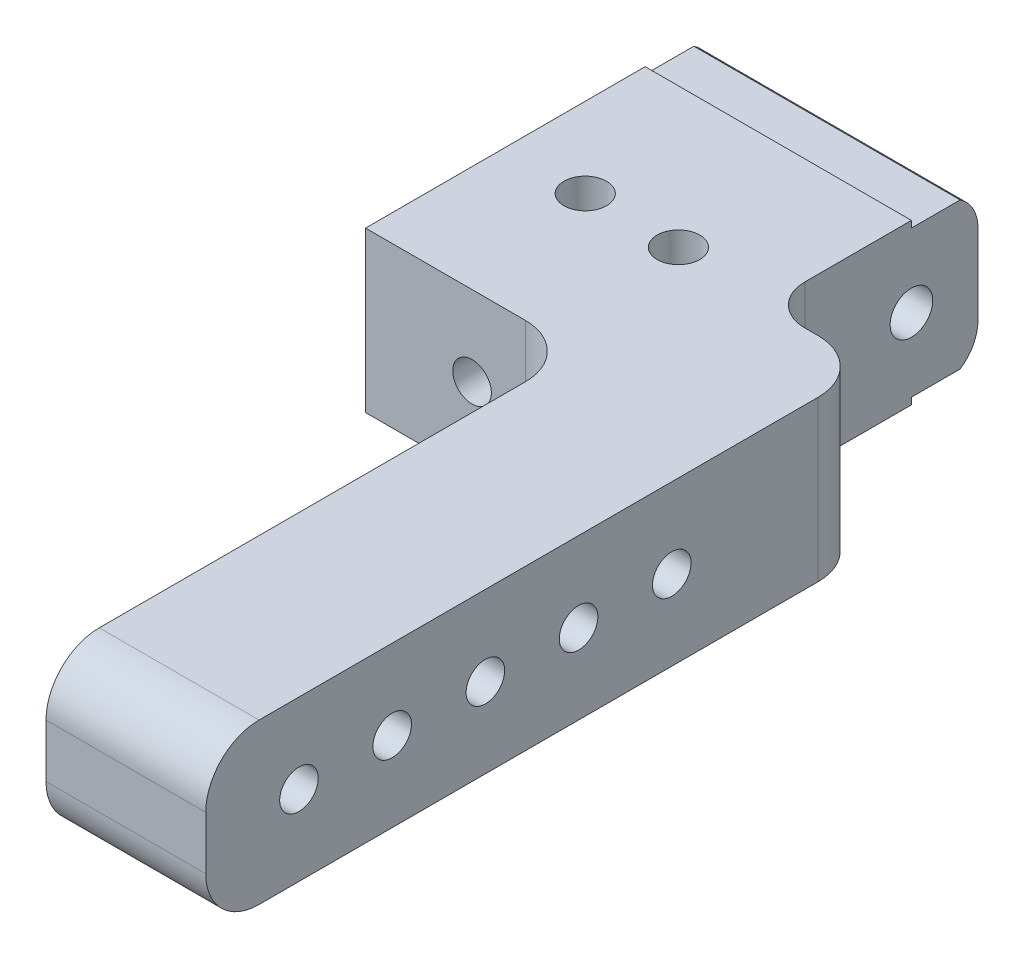
SolidWorks part; units mm, degrees
ref_plane "Front" through (0, 0, 0) normal (0, 0, 1) x (1, 0, 0)
ref_plane "Top" through (0, 0, 0) normal (0, 1, 0) x (1, 0, 0)
ref_plane "Right" through (0, 0, 0) normal (1, 0, 0) x (0, 0, -1)
sketch "Sketch1" plane through (0, 0, 0) normal (0, 0, 1) x (1, 0, 0)
  line L1 (0, 0) -> (20, 0)
  line L2 (0, 0) -> (0, -12)
  line L3 (0, -12) -> (20, -12)
  line L4 (20, 0) -> (20, -12)
  dimension "D1" = 20
  dimension "D2" = 12
extrude "Boss-Extrude1" add sketch "Sketch1" along normal blind 26
sketch "Sketch2" plane through (20, 0, 0) normal (1, 0, 0) x (0, 0, -1)
  line L0 (-26, 0) -> (0, 0) construction
  line L1 (-26, -12) -> (-16, -12)
  line L2 (-26, -12) -> (-26, 0)
  line L3 (-26, 0) -> (-16, 0)
  line L4 (-16, -12) -> (-16, 0)
  dimension "D1" = 10
extrude "Boss-Extrude2" add sketch "Sketch2" along normal blind 8
sketch "Sketch4" plane through (0, 0, 0) normal (0, 1, 0) x (1, 0, 0)
  line L0 (28, -26) -> (0, -26) construction
  line L1 (0, -26) -> (0, 0) construction
  circle A0 centre (13, -15.5) radius 1.6
  circle A1 centre (6, -15.5) radius 1.6
  dimension "D1" = 3.2
  dimension "D2" = 3.2
  dimension "D3" = 7
  dimension "D4" = 10.5
  dimension "D5" = 6
  dimension "D6" = 10.5
extrude "Cut-Extrude2" cut sketch "Sketch4" against normal through all
fillet "Fillet1" radius 3 1 edges at (20, -6, 16)
fillet "Fillet3" radius 3 2 edges at (10, -12, 0) (10, 0, 0)
sketch "Sketch5" plane through (0, 0, 0) normal (-1, 0, 0) x (0, 0, 1)
  line L0 (26, -12) -> (3, -12) construction
  line L1 (5, -12) -> (-4.9767, -12)
  line L2 (5, -12) -> (5, -11.5)
  line L3 (5, -11.5) -> (-4.9767, -11.5)
  line L4 (-4.9767, -12) -> (-4.9767, -11.5)
  line L5 (26, 0) -> (3, 0) construction
  line L6 (5, 0) -> (-7.2599, 0)
  line L7 (5, 0) -> (5, -0.5)
  line L8 (5, -0.5) -> (-7.2599, -0.5)
  line L9 (-7.2599, 0) -> (-7.2599, -0.5)
  line L10 (0, -3) -> (0, -9) construction
  dimension "D1" = 0.5
  dimension "D2" = 0.5
  dimension "D3" = 5
  dimension "D4" = 5
extrude "Cut-Extrude3" cut sketch "Sketch5" against normal through all
sketch "Sketch6" plane through (0, 0, 0) normal (0, 0, -1) x (-1, 0, 0)
  line L1 (-12.75, 7.3758) -> (-7.25, 7.3758)
  line L2 (-12.75, 7.3758) -> (-12.75, -23.1123)
  line L3 (-12.75, -23.1123) -> (-7.25, -23.1123)
  line L4 (-7.25, 7.3758) -> (-7.25, -23.1123)
  dimension "D1" = 5.5
  dimension "D2" = 7.25
extrude "Cut-Extrude4" cut sketch "Sketch6" against normal blind 0.8
sketch "Sketch8" plane through (0, 0, 26) normal (0, 0, 1) x (1, 0, 0)
  line L0 (28, 0) -> (0, 0) construction
  line L1 (28, -12) -> (16, -12)
  line L2 (28, -12) -> (28, 0)
  line L3 (28, 0) -> (16, 0)
  line L4 (16, -12) -> (16, 0)
  dimension "D1" = 12
extrude "Boss-Extrude3" add sketch "Sketch8" along normal blind 40
sketch "Sketch3" plane through (0, 0, 0) normal (-1, 0, 0) x (0, 0, 1)
  line L0 (0, -3) -> (0, -9) construction
  line L2 (26, -12) -> (5, -12) construction
  circle A0 centre (5, -6) radius 1.6
  dimension "D1" = 3.2
  dimension "D2" = 5
  dimension "D6" = 6
extrude "Cut-Extrude1" cut sketch "Sketch3" against normal through all
sketch "Sketch9" plane through (28, 0, 0) normal (1, 0, 0) x (0, 0, -1)
  line L0 (-16, -12) -> (-16, 0) construction
  circle A0 centre (-31, -6) radius 1.45
  circle A1 centre (-38, -6) radius 1.45
  circle A2 centre (-45, -6) radius 1.45
  circle A3 centre (-52, -6) radius 1.45
  circle A4 centre (-59, -6) radius 1.45
  dimension "D1" = 2.9
  dimension "D2" = 15
  dimension "D3" = 5
extrude "Cut-Extrude6" cut sketch "Sketch9" against normal blind 12
fillet "Fillet4" radius 4 1 edges at (16, -6, 26)
sketch "Sketch10" plane through (0, 0, 26) normal (0, 0, 1) x (1, 0, 0)
  line L0 (0, 0) -> (0, -12) construction
  circle A0 centre (8, -6) radius 1.45
  dimension "D1" = 2.9
  dimension "D2" = 8
extrude "Cut-Extrude7" cut sketch "Sketch10" against normal blind 12
fillet "Fillet5" radius 4 1 edges at (28, -6, 16)
fillet "Fillet7" radius 4 2 edges at (22, -12, 66) (22, 0, 66)
